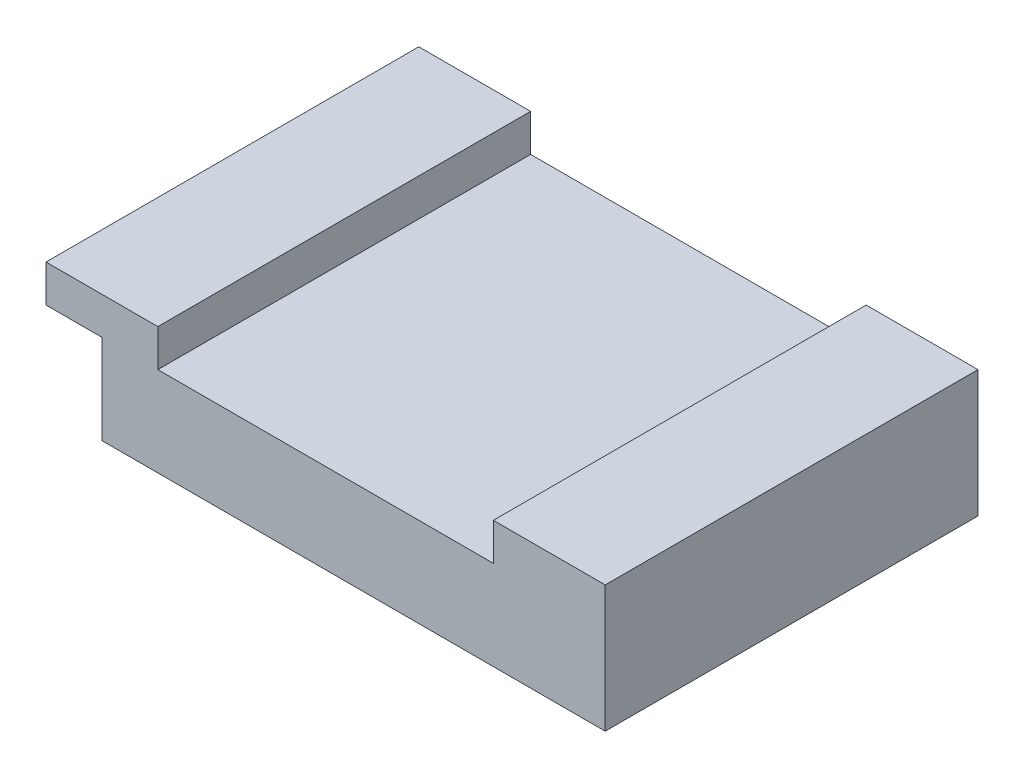
SolidWorks part; units mm, degrees
ref_plane "정면" through (0, 0, 0) normal (0, 0, 1) x (1, 0, 0)
ref_plane "윗면" through (0, 0, 0) normal (0, 1, 0) x (1, 0, 0)
ref_plane "우측면" through (0, 0, 0) normal (1, 0, 0) x (0, 0, -1)
sketch "스케치1" plane through (0, 0, 0) normal (0, 0, 1) x (1, 0, 0)
  line L1 (0, 0) -> (15, 0)
  line L2 (0, 0) -> (0, 5)
  line L3 (0, 5) -> (15, 5)
  line L4 (15, 0) -> (15, 5)
  dimension "D1" = 5
  dimension "D2" = 15
extrude "보스-돌출1" add sketch "스케치1" along normal blind 50
sketch "스케치2" plane through (0, 0, 0) normal (0, -1, 0) x (1, 0, 0)
  line L0 (0, 0) -> (15, 0) construction
  line L1 (15, 50) -> (7.5, 50)
  line L2 (15, 50) -> (15, 0)
  line L3 (15, 0) -> (7.5, 0)
  line L4 (7.5, 50) -> (7.5, 0)
  dimension "D1" = 7.5
extrude "보스-돌출2" add sketch "스케치2" along normal blind 12
sketch "스케치3" plane through (15, 0, 0) normal (1, 0, 0) x (0, 0, -1)
  line L0 (0, -12) -> (0, 5) construction
  line L1 (-50, -12) -> (0, -12)
  line L2 (-50, -12) -> (-50, 0)
  line L3 (-50, 0) -> (0, 0)
  line L4 (0, -12) -> (0, 0)
  dimension "D1" = 12
extrude "보스-돌출3" add sketch "스케치3" along normal blind 60
sketch "스케치4" plane through (0, 0, 0) normal (0, 1, 0) x (1, 0, 0)
  line L0 (75, -50) -> (15, -50) construction
  line L1 (75, 0) -> (60, 0)
  line L2 (75, 0) -> (75, -50)
  line L3 (75, -50) -> (60, -50)
  line L4 (60, 0) -> (60, -50)
  dimension "D1" = 15
extrude "보스-돌출4" add sketch "스케치4" along normal blind 5
